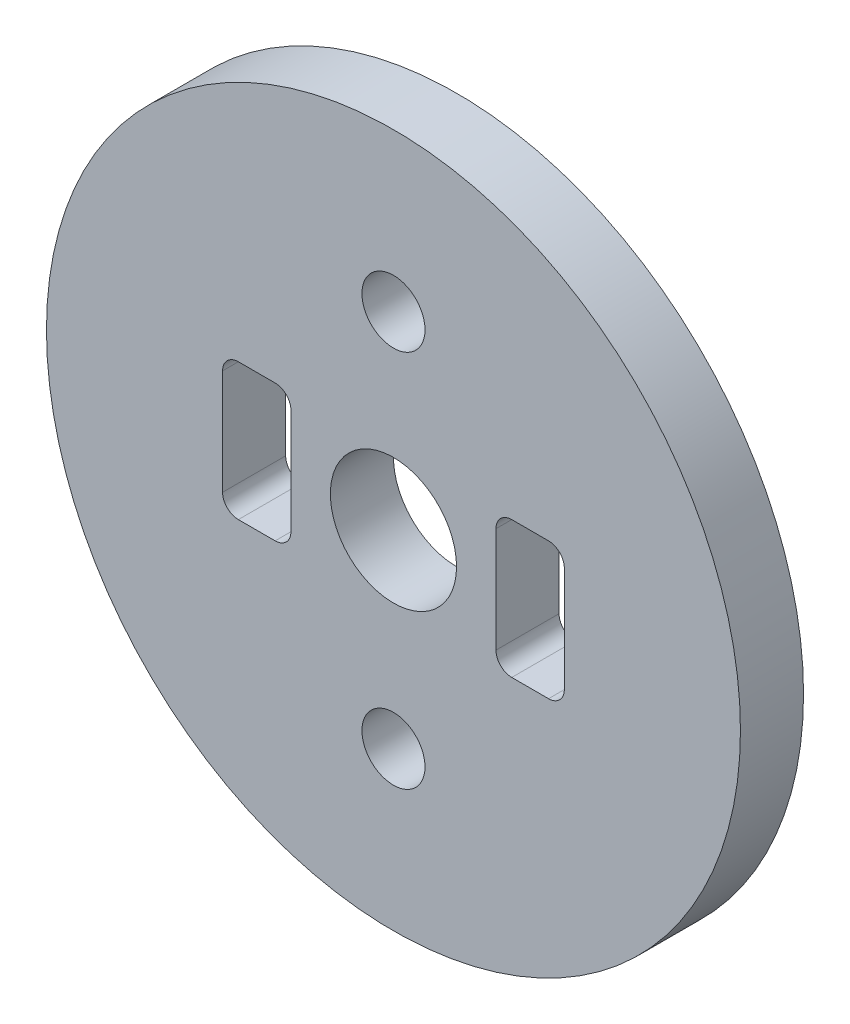
SolidWorks part; units mm, degrees
ref_plane "Alzado" through (0, 0, 0) normal (0, 0, 1) x (1, 0, 0)
ref_plane "Planta" through (0, 0, 0) normal (0, 1, 0) x (1, 0, 0)
ref_plane "Vista lateral" through (0, 0, 0) normal (1, 0, 0) x (0, 0, -1)
sketch "Model" plane through (0, 0, 0) normal (0, 0, 1) x (1, 0, 0)
  line L0 (223.1228, 245.202) -> (221.3728, 245.202)
  line L1 (223.8728, 239.452) -> (223.8728, 244.452)
  line L2 (221.3728, 238.702) -> (223.1228, 238.702)
  line L3 (220.6228, 244.452) -> (220.6228, 239.452)
  line L4 (208.3728, 245.202) -> (210.1228, 245.202)
  line L5 (207.6228, 239.452) -> (207.6228, 244.452)
  line L6 (210.1228, 238.702) -> (208.3728, 238.702)
  line L7 (210.8728, 244.452) -> (210.8728, 239.452)
  circle A0 centre (215.7478, 241.952) radius 3
  circle A1 centre (215.7478, 232.952) radius 1.5
  circle A2 centre (215.7478, 250.952) radius 1.5
  arc A3 (221.3728, 245.202) -> (220.6228, 244.452) centre (221.3728, 244.452) ccw
  arc A4 (223.8728, 244.452) -> (223.1228, 245.202) centre (223.1228, 244.452) ccw
  arc A5 (223.1228, 238.702) -> (223.8728, 239.452) centre (223.1228, 239.452) ccw
  arc A6 (220.6228, 239.452) -> (221.3728, 238.702) centre (221.3728, 239.452) ccw
  arc A7 (210.8728, 244.452) -> (210.1228, 245.202) centre (210.1228, 244.452) ccw
  arc A8 (208.3728, 245.202) -> (207.6228, 244.452) centre (208.3728, 244.452) ccw
  arc A9 (207.6228, 239.452) -> (208.3728, 238.702) centre (208.3728, 239.452) ccw
  arc A10 (210.1228, 238.702) -> (210.8728, 239.452) centre (210.1228, 239.452) ccw
  circle A11 centre (215.7478, 241.952) radius 16.5
extrude "Saliente-Extruir1" add sketch "Model" along normal blind 3
